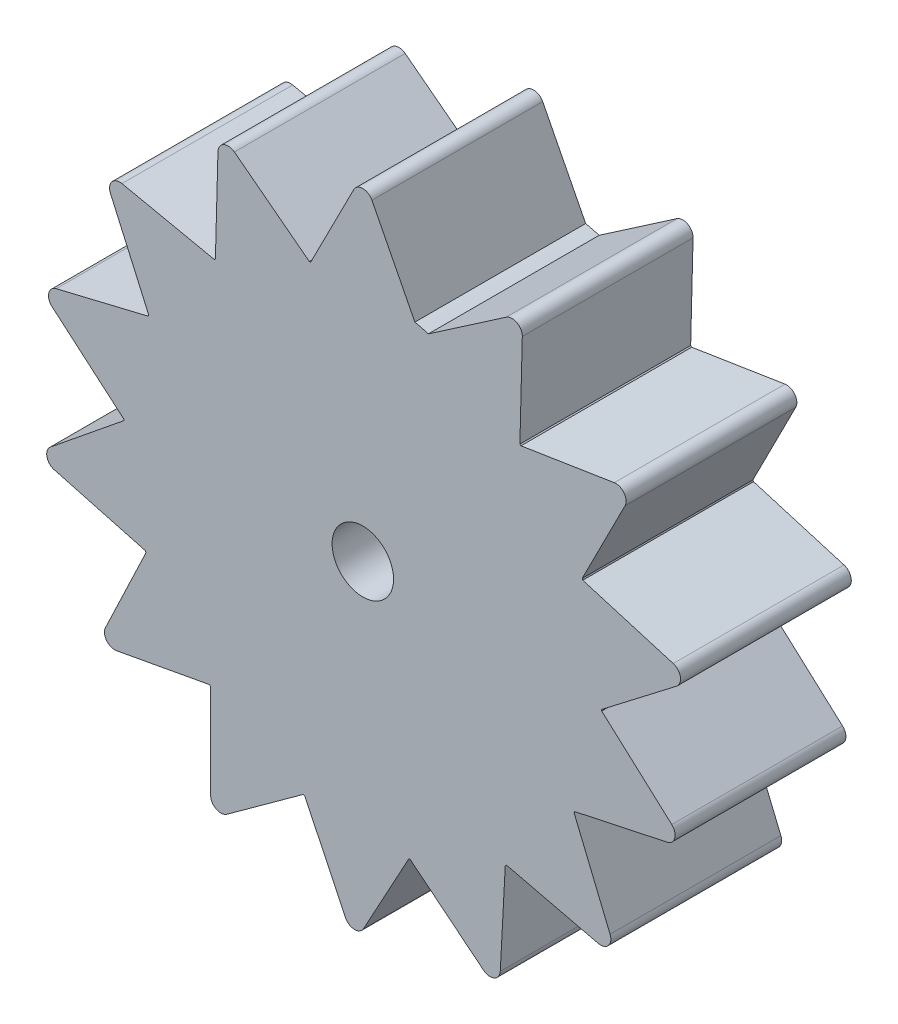
SolidWorks part; units mm, degrees
ref_plane "Front Plane" through (0, 0, 0) normal (0, 0, 1) x (1, 0, 0)
ref_plane "Top Plane" through (0, 0, 0) normal (0, 1, 0) x (1, 0, 0)
ref_plane "Right Plane" through (0, 0, 0) normal (1, 0, 0) x (0, 0, -1)
sketch "Sketch1" plane through (0, 0, 0) normal (0, 0, 1) x (1, 0, 0)
  circle A0 centre (0, 0) radius 0.9
  circle A1 centre (0, 0) radius 7
  dimension "D1" = 14
  dimension "D2" = 1.8
extrude "Boss-Extrude1" add sketch "Sketch1" along normal blind 5
sketch "Sketch2" plane through (0, 0, 5) normal (0, 0, 1) x (1, 0, 0)
  line L0 (0, 0) -> (0, 8.2606) construction
  line L1 (0, 8.2606) -> (0, 9.8165) construction
  line L2 (-0.2672, 9.2934) -> (-1.5243, 6.832)
  line L3 (0.2672, 9.2934) -> (1.5243, 6.832)
  circle A0 centre (0, 0) radius 7 construction
  circle A1 centre (0, 0) radius 7
  arc A2 (-0.2672, 9.2934) -> (0.2672, 9.2934) centre (0, 9.157) cw
  circle A3 centre (0, 0) radius 7
  circle A4 centre (0, 0) radius 7
  circle M2 centre (0, 0) radius 7
  dimension "D2" = 0.3
  dimension "D1" = 0
extrude "Boss-Extrude2" add sketch "Sketch2" against normal up to surface (5 mm away) contours L3 L2 M2
pattern_circular "CirPattern1" count 14 every 25.5 about axis through (0, 0, 0) along (0, 0, 1) of "Boss-Extrude2"
